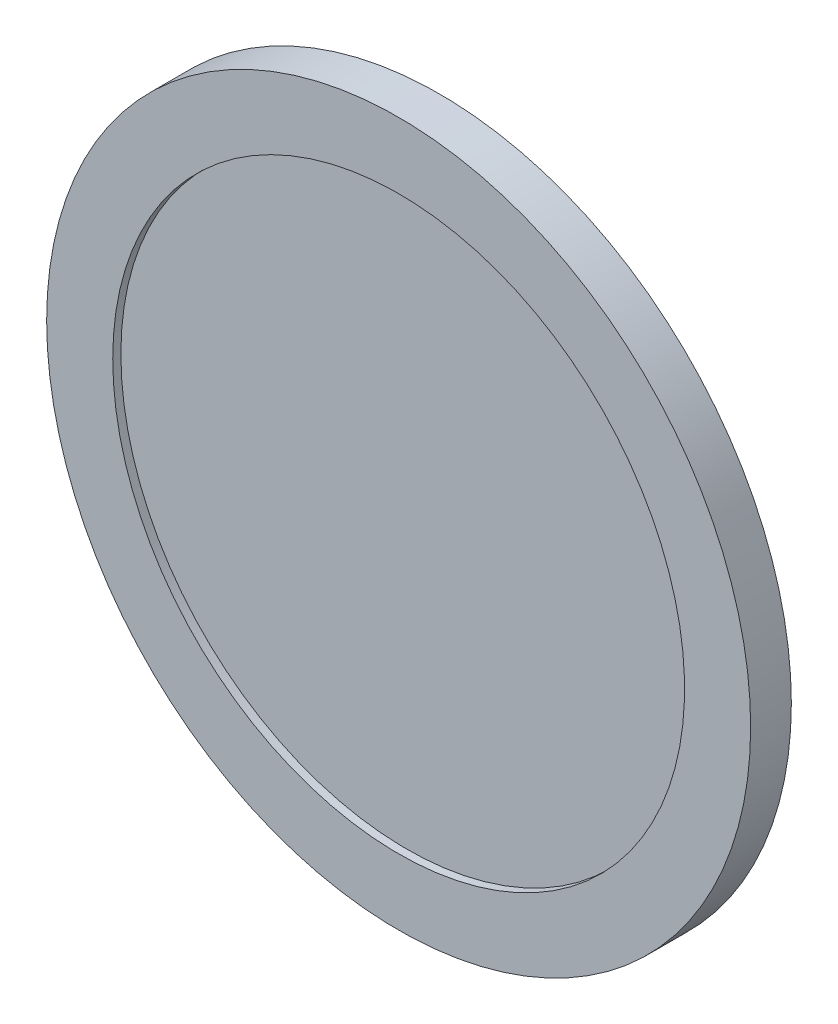
SolidWorks part; units mm, degrees
ref_plane "Plan de face" through (0, 0, 0) normal (0, 0, 1) x (1, 0, 0)
ref_plane "Plan de dessus" through (0, 0, 0) normal (0, 1, 0) x (1, 0, 0)
ref_plane "Plan de droite" through (0, 0, 0) normal (1, 0, 0) x (0, 0, -1)
sketch "Esquisse1" plane through (0, 0, 0) normal (1, 0, 0) x (0, 0, -1)
  line L0 (0, 0) -> (0, 70.2607)
  line L1 (0, 70.2607) -> (-2, 70.2607)
  line L2 (-2, 70.2607) -> (-2, 86.5)
  line L3 (-2, 86.5) -> (8, 86.5)
  line L4 (8, 86.5) -> (8, 70.2607)
  line L5 (8, 70.2607) -> (6, 70.2607)
  line L6 (6, 70.2607) -> (6, 0)
  line L9 (6, 0) -> (0, 0)
  dimension "D1" = 86.5
  dimension "D2" = 10
  dimension "D3" = 2
revolve "Révolution1" add sketch "Esquisse1" angle 360 about L9
